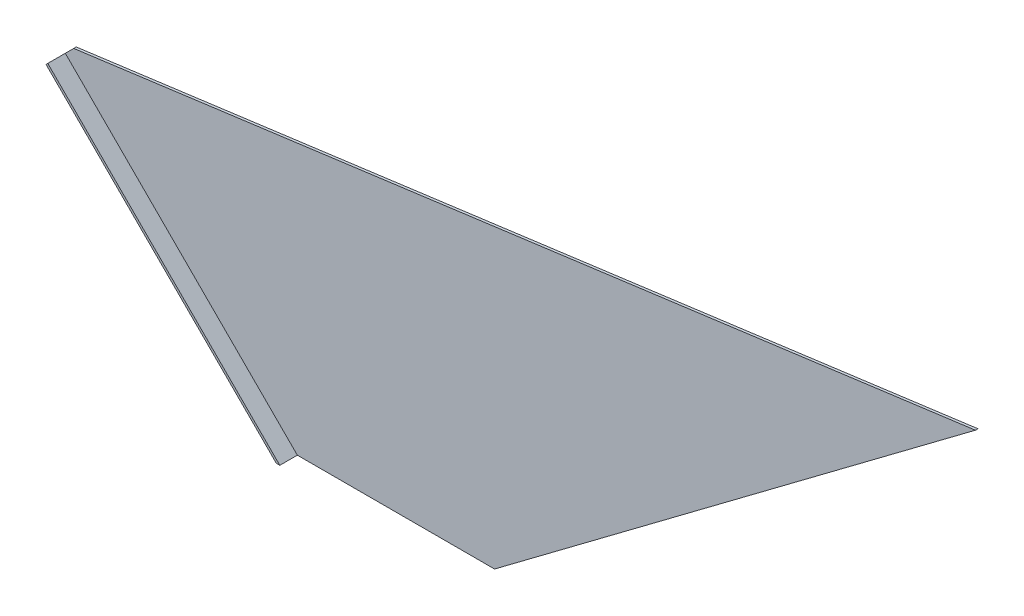
SolidWorks part; units mm, degrees
ref_plane "Front Plane" through (0, 0, 0) normal (0, 0, 1) x (1, 0, 0)
ref_plane "Top Plane" through (0, 0, 0) normal (0, 1, 0) x (1, 0, 0)
ref_plane "Right Plane" through (0, 0, 0) normal (1, 0, 0) x (0, 0, -1)
sketch "Sketch2" plane through (0, 0, 0) normal (0, 0, 1) x (1, 0, 0)
  line L0 (0, 0) -> (114.3, 0)
  line L1 (114.3, 0) -> (419.1, 228.6)
  line L2 (419.1, 228.6) -> (-152.4, 152.4)
  line L3 (-152.4, 152.4) -> (0, 0)
  dimension "D1" = 114.3
  dimension "D2" = 228.6
  dimension "D3" = 304.8
  dimension "D4" = 152.4
  dimension "D5" = 152.4
extrude "Boss-Extrude1" add sketch "Sketch2" along normal blind 1.5875
ref_plane "Plane1" through (-152.4, 152.4, 0) normal (-0.7071, 0.7071, 0) x (0, 0, -1)
sketch "Sketch6" plane through (-152.4, 152.4, 0) normal (-0.7071, 0.7071, 0) x (0, 0, -1)
  line L0 (0, 7.5438) -> (0, 7.8613)
  line L1 (-1.27, 9.1313) -> (-12.7, 9.1313)
  line L2 (-12.7, 9.1313) -> (-12.7, 7.5438)
  line L3 (-12.7, 7.5438) -> (-1.5875, 7.5438)
  line L4 (0, 7.5438) -> (0, 0)
  line L5 (0, 0) -> (-1.5875, 0)
  line L6 (-1.5875, 0) -> (-1.5875, 7.5438)
  arc A0 (0, 7.8613) -> (-1.27, 9.1313) centre (-1.27, 7.8613) ccw
  point P7 (0, 9.1313)
  dimension "D3" = 1.27
  dimension "D1" = 12.7
  dimension "D2" = 1.5875
  dimension "D4" = 9.1313
  dimension "D5" = 1.5875
extrude "Boss-Extrude2" add sketch "Sketch6" against normal up to vertex (215.5261 mm away) up to point (0, 0, 0)
sketch "Sketch7" plane through (0, 0, 0) normal (0, 0, -1) x (-1, 0, 0)
  line L0 (0, 0) -> (12.9136, 0)
  line L1 (6.4568, -6.4568) -> (158.8568, 145.9432) construction
  line L2 (12.9136, 0) -> (6.4568, -6.4568)
  line L3 (6.4568, -6.4568) -> (0, 0)
extrude "Cut-Extrude1" cut sketch "Sketch7" against normal up to surface (12.7 mm away) up to face at (-82.0955, 70.3045, 12.7)
